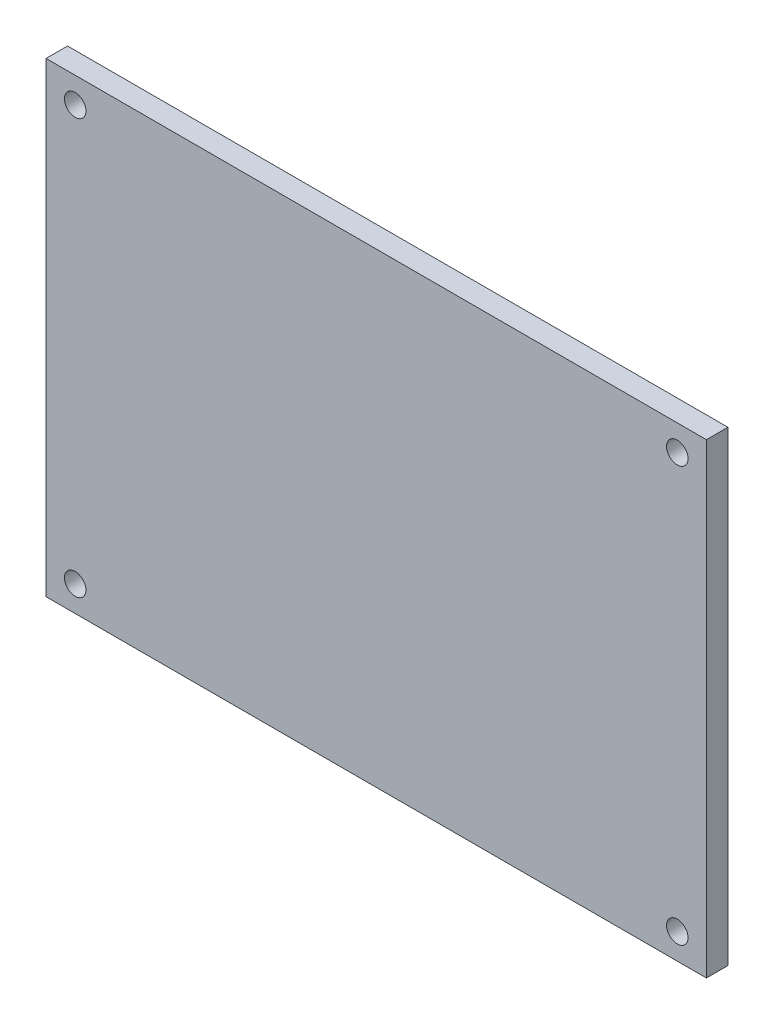
SolidWorks part; units mm, degrees
ref_plane "前视基准面" through (0, 0, 0) normal (0, 0, 1) x (1, 0, 0)
ref_plane "上视基准面" through (0, 0, 0) normal (0, 1, 0) x (1, 0, 0)
ref_plane "右视基准面" through (0, 0, 0) normal (1, 0, 0) x (0, 0, -1)
other "Configuration Table"
sketch "草图1" plane through (0, 0, 0) normal (0, 0, 1) x (1, 0, 0)
  line L1 (-46.0375, -32.5) -> (46.0375, -32.5)
  line L2 (-46.0375, -32.5) -> (-46.0375, 32.5)
  line L3 (-46.0375, 32.5) -> (46.0375, 32.5)
  line L4 (46.0375, -32.5) -> (46.0375, 32.5)
  line L5 (0, 32.5) -> (0, -32.5) construction
  line L6 (-46.0375, 0) -> (46.0375, 0) construction
  line L7 (-41.9735, -28.92) -> (41.9735, -28.92)
  line L8 (-41.9735, -28.92) -> (-41.9735, 28.92)
  line L9 (-41.9735, 28.92) -> (41.9735, 28.92)
  line L10 (41.9735, -28.92) -> (41.9735, 28.92)
  line L11 (-41.9735, -28.92) -> (41.9735, 28.92) construction
  line L12 (-41.9735, 28.92) -> (41.9735, -28.92) construction
  circle A0 centre (-41.9735, 28.92) radius 1.5
  circle A1 centre (41.9735, 28.92) radius 1.5
  circle A2 centre (41.9735, -28.92) radius 1.5
  circle A3 centre (-41.9735, -28.92) radius 1.5
  point P0 (0, 0)
  point P4 (0, 0)
  dimension "D5" = 3
  dimension "D6" = 3
  dimension "D7" = 3
  dimension "D8" = 3
  dimension "D1" = 92.075
  dimension "D2" = 65
  dimension "D3" = 83.947
  dimension "D4" = 57.84
extrude "凸台-拉伸1" add sketch "草图1" along normal blind 3 contours A3 L7 A2 L10 A1 L9 A0 L8 | L1 L4 L3 L2 A3 L8 A0 L9 A1 L10 A2 L7
